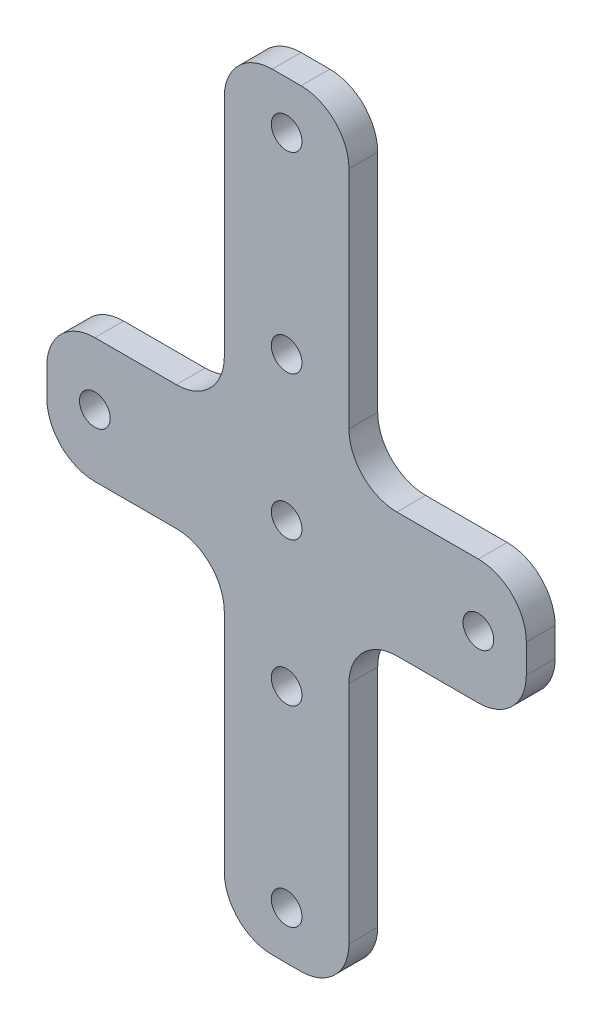
SolidWorks part; units mm, degrees
ref_plane "前视基准面" through (0, 0, 0) normal (0, 0, 1) x (1, 0, 0)
ref_plane "上视基准面" through (0, 0, 0) normal (0, 1, 0) x (1, 0, 0)
ref_plane "右视基准面" through (0, 0, 0) normal (1, 0, 0) x (0, 0, -1)
sketch "草图1" plane through (0, 0, 0) normal (0, 0, 1) x (1, 0, 0)
  line L0 (20, 0) -> (-20, 0) construction
  line L1 (0, 0) -> (0, 35) construction
  line L2 (-6.5, 6.5) -> (-25, 6.5)
  line L3 (-25, 6.5) -> (-25, -6.5)
  line L4 (-25, -6.5) -> (25, -6.5)
  line L5 (25, -6.5) -> (25, 6.5)
  line L6 (25, 6.5) -> (6.5, 6.5)
  line L7 (6.5, 6.5) -> (6.5, 40)
  line L8 (6.5, 40) -> (-6.5, 40)
  line L9 (-6.5, 40) -> (-6.5, 6.5)
  circle A0 centre (0, 35) radius 1.6
  circle A1 centre (0, 15) radius 1.6
  circle A2 centre (0, 0) radius 1.6
  circle A3 centre (20, 0) radius 1.6
  circle A4 centre (-20, 0) radius 1.6
  point P4 (0, 0)
  dimension "D1" = 3.2
  dimension "D2" = 15
  dimension "D3" = 20
  dimension "D7" = 5
  dimension "D9" = 5
  dimension "D4" = 40
  dimension "D5" = 6.5
  dimension "D6" = 6.5
  dimension "D8" = 6.5
  dimension "D10" = 6.5
  dimension "D11" = 6.5
  dimension "D12" = 5
extrude "凸台-拉伸1" add sketch "草图1" along normal blind 3
fillet "圆角1" radius 5 8 edges at (-6.5, 40, 1.5) (6.5, 40, 1.5) (25, 6.5, 1.5) (25, -6.5, 1.5) (-25, -6.5, 1.5) (-25, 6.5, 1.5) (-6.5, 6.5, 1.5) (6.5, 6.5, 1.5)
mirror "镜向1" about plane through (0, 0, 0) normal (0, 1, 0) of bodies 101
